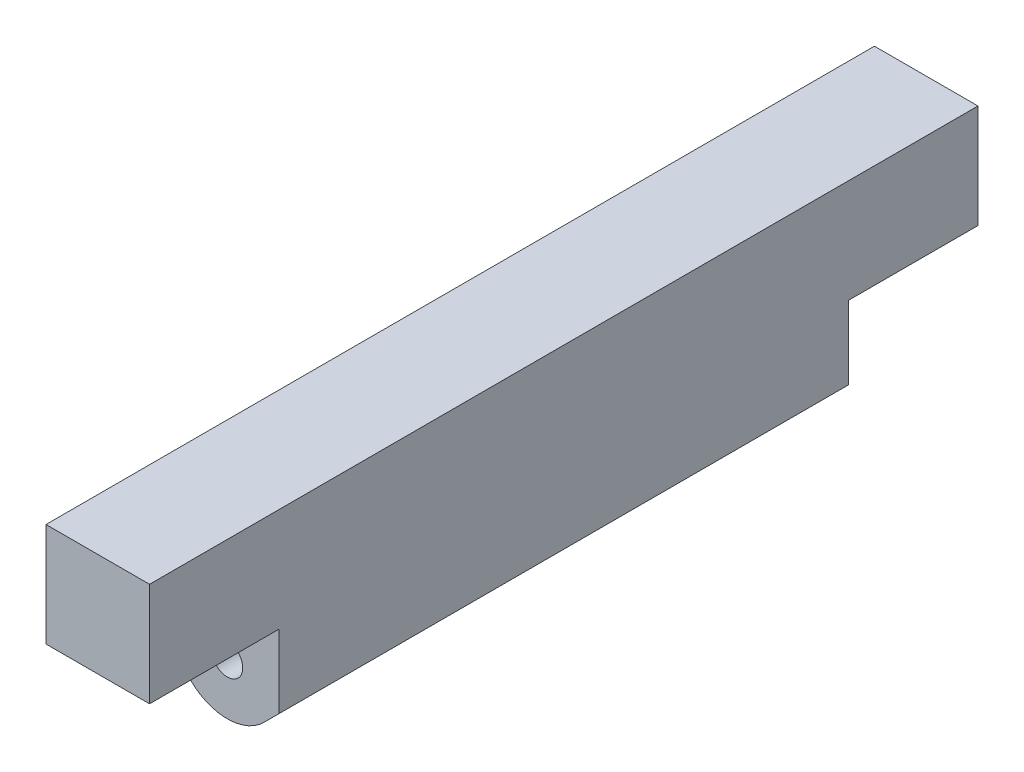
SolidWorks part; units mm, degrees
ref_plane "前视基准面" through (0, 0, 0) normal (0, 0, 1) x (1, 0, 0)
ref_plane "上视基准面" through (0, 0, 0) normal (0, 1, 0) x (1, 0, 0)
ref_plane "右视基准面" through (0, 0, 0) normal (1, 0, 0) x (0, 0, -1)
sketch "草图1" plane through (0, 0, 0) normal (0, 0, 1) x (1, 0, 0)
  line L1 (-2.5, -5) -> (2.5, -5)
  line L2 (-2.5, -5) -> (-2.5, 5)
  line L3 (-2.5, 5) -> (2.5, 5)
  line L4 (2.5, -5) -> (2.5, 5)
  line L5 (-2.5, -5) -> (2.5, 5) construction
  line L6 (-2.5, 5) -> (2.5, -5) construction
  point P0 (0, 0)
  dimension "D1" = 5
  dimension "D2" = 10
extrude "凸台-拉伸1" add sketch "草图1" along normal blind 27.5
ref_plane "基准面4" through (0, 0, 13.75) normal (0, 0, 1) x (1, 0, 0)
sketch "草图2" plane through (0, 0, 13.75) normal (0, 0, 1) x (1, 0, 0)
  line L0 (-2.5, 5) -> (2.5, 5)
  line L1 (2.5, 5) -> (2.5, 0)
  line L2 (2.5, -5) -> (2.5, 5) construction
  line L3 (2.5, 0) -> (-2.5, 0)
  line L4 (-2.5, 5) -> (-2.5, -5) construction
  line L5 (-2.5, 0) -> (-2.5, 5)
extrude "凸台-拉伸2" add sketch "草图2" along normal mid plane 40
sketch "草图3" plane through (0, 0, 0) normal (0, 0, -1) x (-1, 0, 0)
  line L0 (2.5, 0) -> (-2.5, 0) construction
  line L1 (2.5, 0) -> (2.5, -5) construction
  circle A0 centre (0, -2.5) radius 0.75
  dimension "D1" = 1.5
  dimension "D2" = 2.5
  dimension "D3" = 2.5
extrude "切除-拉伸1" cut sketch "草图3" against normal blind 6
mirror "镜向1" about plane through (0, 0, 13.75) normal (0, 0, 1) of "切除-拉伸1"
sketch "草图4" plane through (0, 0, 0) normal (0, 0, -1) x (-1, 0, 0)
  line L0 (0, -2.5) -> (-1.7678, -4.2678) construction
  line L1 (-1.7678, -4.2678) -> (-2.5, -3.5355)
  line L2 (2.5, 0) -> (2.5, -5) construction
  line L4 (-2.5, -3.5355) -> (-2.5, 0)
  line L5 (-2.5, 0) -> (2.5, 0)
  line L6 (2.5, -3.5355) -> (2.5, 0)
  line L7 (-1.7678, -4.2678) -> (2.5, 0) construction
  line L8 (-2.5, 0) -> (1.7678, -4.2678) construction
  line L9 (2.5, 5) -> (2.5, 0) construction
  line L10 (0, -2.5) -> (0, -3.0827) construction
  line L11 (1.7678, -4.2678) -> (2.5, -3.5355)
  line L12 (-2.5, -3.5355) -> (-2.5, -5)
  line L13 (-2.5, -5) -> (2.5, -5)
  line L14 (2.5, -5) -> (2.5, -3.5355)
  arc A0 (-1.7678, -4.2678) -> (1.7678, -4.2678) centre (0, -2.5) ccw
  line M5 (2.5, -5) -> (2.5, 0)
  line M7 (-2.5, 0) -> (-2.5, -5)
  line M8 (-2.5, -5) -> (2.5, -5)
  dimension "D1" = 2.5
  dimension "D2" = 45
extrude "切除-拉伸2" cut sketch "草图4" against normal up to surface (27.5 mm away) contours A0 L1 M7 M8 | A0 L13 L11 M5 up to face at (-0.75, -2.5, 27.5)
